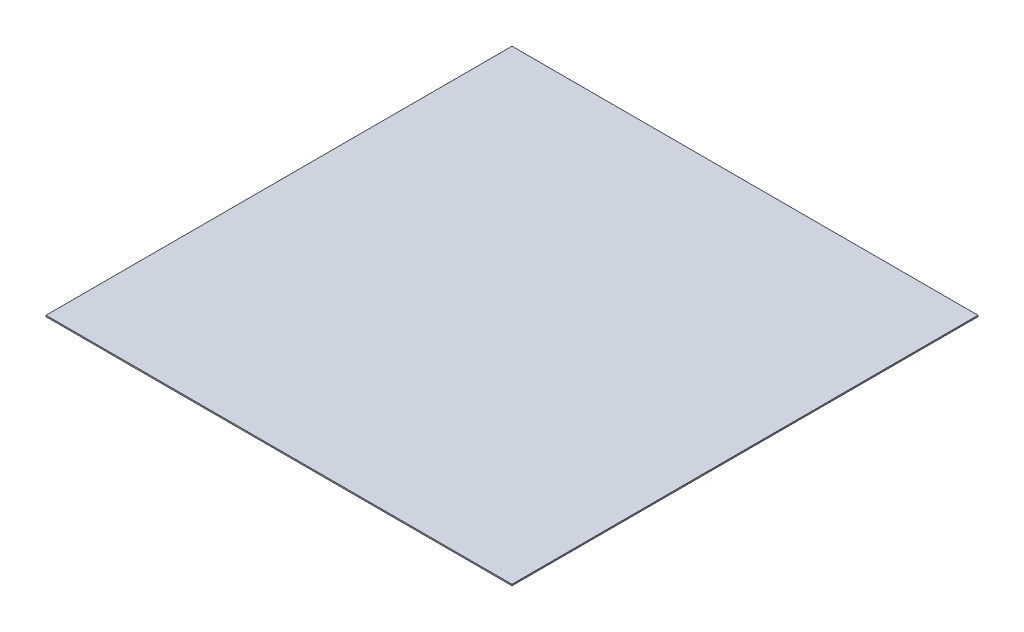
SolidWorks part; units mm, degrees
ref_plane "Front Plane" through (0, 0, 0) normal (0, 0, 1) x (1, 0, 0)
ref_plane "Top Plane" through (0, 0, 0) normal (0, 1, 0) x (1, 0, 0)
ref_plane "Right Plane" through (0, 0, 0) normal (1, 0, 0) x (0, 0, -1)
sketch "Sketch1" plane through (0, 0, 0) normal (0, 1, 0) x (1, 0, 0)
  line L1 (0, 0) -> (914.4, 0)
  line L2 (0, 0) -> (0, 914.4)
  line L3 (0, 914.4) -> (914.4, 914.4)
  line L4 (914.4, 0) -> (914.4, 914.4)
  dimension "D1" = 914.4
  dimension "D2" = 914.4
extrude "Boss-Extrude1" add sketch "Sketch1" along normal blind 2.54
